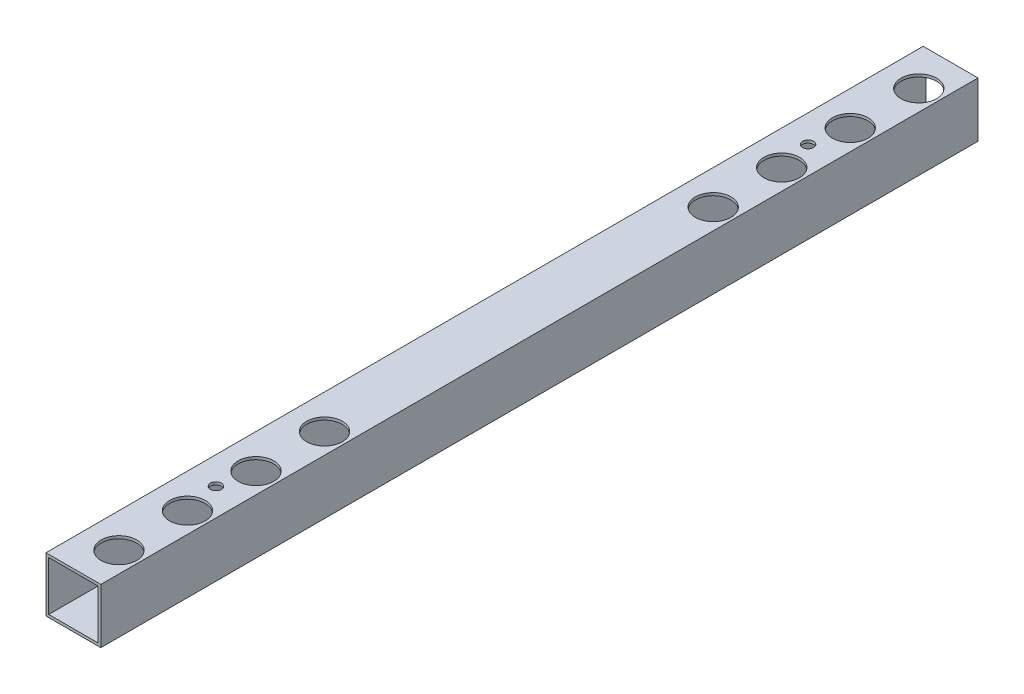
SolidWorks part; units mm, degrees
ref_plane "前视基准面" through (0, 0, 0) normal (0, 0, 1) x (1, 0, 0)
ref_plane "上视基准面" through (0, 0, 0) normal (0, 1, 0) x (1, 0, 0)
ref_plane "右视基准面" through (0, 0, 0) normal (1, 0, 0) x (0, 0, -1)
sketch "草图1" plane through (0, 0, 0) normal (0, 0, 1) x (1, 0, 0)
  line L1 (10, 10) -> (-10, 10)
  line L2 (10, 10) -> (10, -10)
  line L3 (10, -10) -> (-10, -10)
  line L4 (-10, 10) -> (-10, -10)
  line L5 (10, 10) -> (-10, -10) construction
  line L6 (10, -10) -> (-10, 10) construction
  line L7 (9, 9) -> (-9, 9)
  line L8 (9, 9) -> (9, -9)
  line L9 (9, -9) -> (-9, -9)
  line L10 (-9, 9) -> (-9, -9)
  line L11 (9, 9) -> (-9, -9) construction
  line L12 (9, -9) -> (-9, 9) construction
  point P0 (0, 0)
  point P6 (0, 0)
extrude "凸台-拉伸1" add sketch "草图1" along normal mid plane 320 contours L1 L4 L3 L2
hole_wizard "Ø5.0 (5) 直径孔1" positions "草图3" profile "草图2" hole size "Ø5.0" standard "GB"
sketch "草图3" plane through (0, -10, 0) normal (0, -1, 0) x (-1, 0, 0)
  line L0 (0, 0) -> (0, 145.9)
  line L8 (-10, 145.9) -> (-2.5, 145.9)
  line L9 (-10, -160) -> (-10, 160) construction
  line L10 (-2.5, 145.9) -> (-2.5, 120.9)
  point P44 (-2.5, 145.9)
  point P47 (-2.5, 120.9)
sketch "草图2" plane through (2.5, -10, -145.9) normal (1, 0, 0) x (0, 0, -1)
  line L0 (0, 0) -> (0, 20)
  line L1 (0, 20) -> (2.5, 20)
  line L2 (2.5, 20) -> (2.5, 0)
  line L5 (2.5, 0) -> (0, 0)
  line L11 (0, -6.35) -> (0, 107.95) construction
  dimension "通孔孔直径" = 5
  dimension "通孔孔深度" = 20
pattern_linear "阵列(线性)1" count 2 spacing 50 along (0, 0, 1) of "Ø5.0 (5) 直径孔1"
ref_plane "基准面1" through (0, 0, 0) normal (0, 0, -1) x (-1, 0, 0)
mirror "镜向1" about plane through (0, 0, 0) normal (0, 0, -1) of "阵列(线性)1", "Ø5.0 (5) 直径孔1"
hole_wizard "Ø4.0 (4) 直径孔1" positions "草图5" profile "草图4" hole size "Ø4.0" standard "GB" end condition through all
sketch "草图5" plane through (0, -10, 0) normal (0, -1, 0) x (-1, 0, 0)
  line L1 (0, 0) -> (0, -108)
  point P8 (0, -108)
sketch "草图4" plane through (0, -10, 108) normal (1, 0, 0) x (0, 0, -1)
  line L0 (0, 0) -> (0, 20)
  line L1 (0, 20) -> (2, 20)
  line L2 (2, 20) -> (2, 0)
  line L5 (2, 0) -> (0, 0)
  line L11 (0, -6.35) -> (0, 107.95) construction
  dimension "通孔孔直径" = 4
  dimension "通孔孔深度" = 20
mirror "镜向2" about plane through (0, 0, 0) normal (0, 0, -1) of "Ø4.0 (4) 直径孔1"
hole_wizard "Ø13.0 (13) 直径孔1" positions "草图7" profile "草图6" hole size "Ø13.0" standard "GB"
sketch "草图7" plane through (0, 9, 0) normal (0, -1, 0) x (-1, 0, 0)
  point P0 (-2.5, 145.9)
  point P3 (-2.5, 120.9)
  point P6 (-2.5, 95.9)
  point P9 (-2.5, 70.9)
sketch "草图6" plane through (2.5, 9, -145.9) normal (1, 0, 0) x (0, 0, -1)
  line L0 (0, 0) -> (0, 1)
  line L1 (0, 1) -> (6.5, 1)
  line L2 (6.5, 1) -> (6.5, 0)
  line L5 (6.5, 0) -> (0, 0)
  line L11 (0, -6.35) -> (0, 107.95) construction
  dimension "通孔孔直径" = 13
  dimension "通孔孔深度" = 1
mirror "镜向3" about plane through (0, 0, 0) normal (0, 0, -1) of "Ø13.0 (13) 直径孔1"
